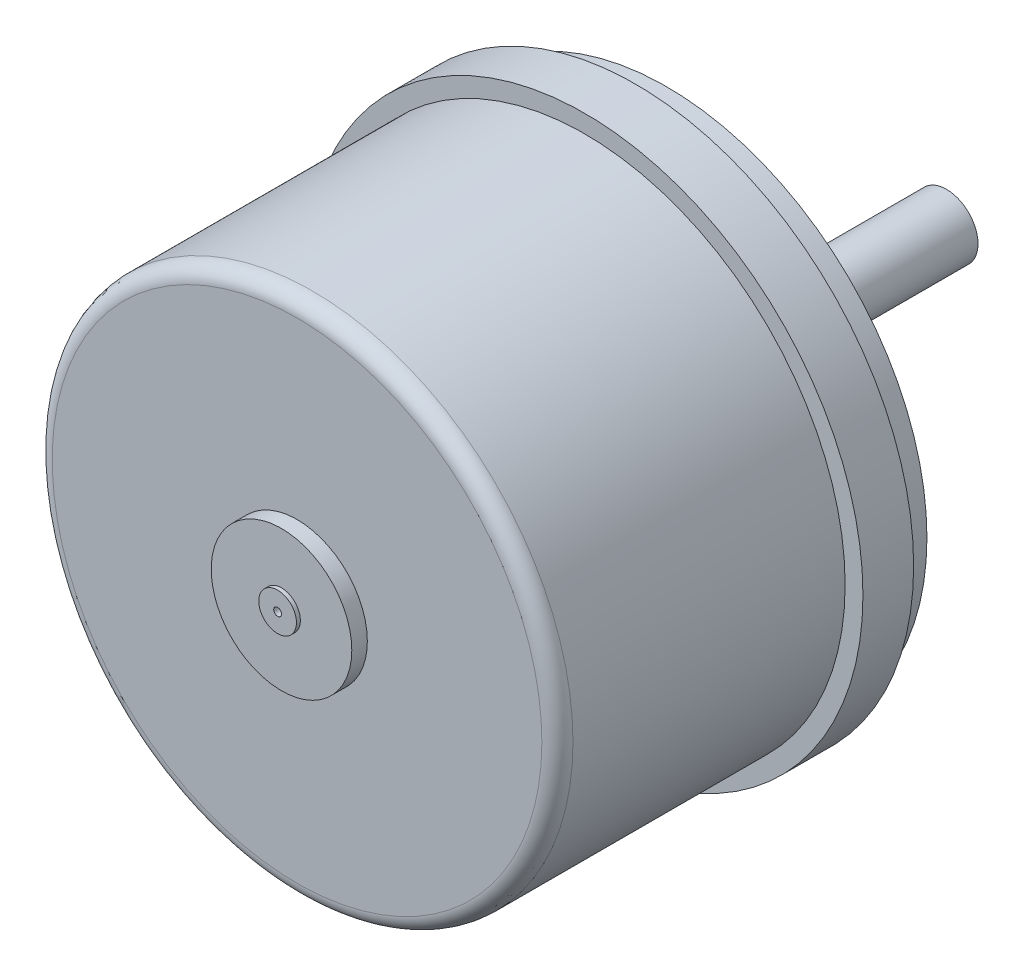
SolidWorks part; units mm, degrees
ref_plane "Alzado" through (0, 0, 0) normal (0, 0, 1) x (1, 0, 0)
ref_plane "Planta" through (0, 0, 0) normal (0, 1, 0) x (1, 0, 0)
ref_plane "Vista lateral" through (0, 0, 0) normal (1, 0, 0) x (0, 0, -1)
sketch "Croquis1" plane through (0, 0, 0) normal (0, 0, 1) x (1, 0, 0)
  circle A0 centre (0, 0) radius 33.485
  dimension "D1" = 66.97
extrude "Saliente-Extruir1" add sketch "Croquis1" along normal mid plane 4
sketch "Croquis2" plane through (0, 0, 2) normal (0, 0, 1) x (1, 0, 0)
  circle A0 centre (0, 0) radius 35.775
  dimension "D1" = 71.55
extrude "Saliente-Extruir2" add sketch "Croquis2" along normal blind 6.52
sketch "Croquis3" plane through (0, 0, 8.52) normal (0, 0, 1) x (1, 0, 0)
  circle A0 centre (0, 0) radius 33.485
  dimension "D1" = 66.97
extrude "Saliente-Extruir3" add sketch "Croquis3" along normal blind 37
sketch "Croquis4" plane through (0, 0, 45.52) normal (0, 0, 1) x (1, 0, 0)
  circle A0 centre (0, 0) radius 9.04
  dimension "D1" = 18.08
extrude "Saliente-Extruir4" add sketch "Croquis4" along normal blind 2
sketch "Croquis5" plane through (0, 0, 47.52) normal (0, 0, 1) x (1, 0, 0)
  circle A0 centre (0, 0) radius 2.425
  dimension "D1" = 4.85
extrude "Saliente-Extruir5" add sketch "Croquis5" along normal blind 0.5
sketch "Croquis6" plane through (0, 0, 48.02) normal (0, 0, 1) x (1, 0, 0)
  circle A0 centre (0, 0) radius 0.5
  dimension "D1" = 1
extrude "Cortar-Extruir1" cut sketch "Croquis6" against normal blind 1
sketch "Croquis7" plane through (0, 0, -2) normal (0, 0, -1) x (-1, 0, 0)
  circle A0 centre (0, 0) radius 4.05
  dimension "D1" = 8.1
extrude "Saliente-Extruir6" add sketch "Croquis7" along normal blind 36
fillet "Redondeo2" radius 2 1 edges at (33.485, 0, 45.52)
